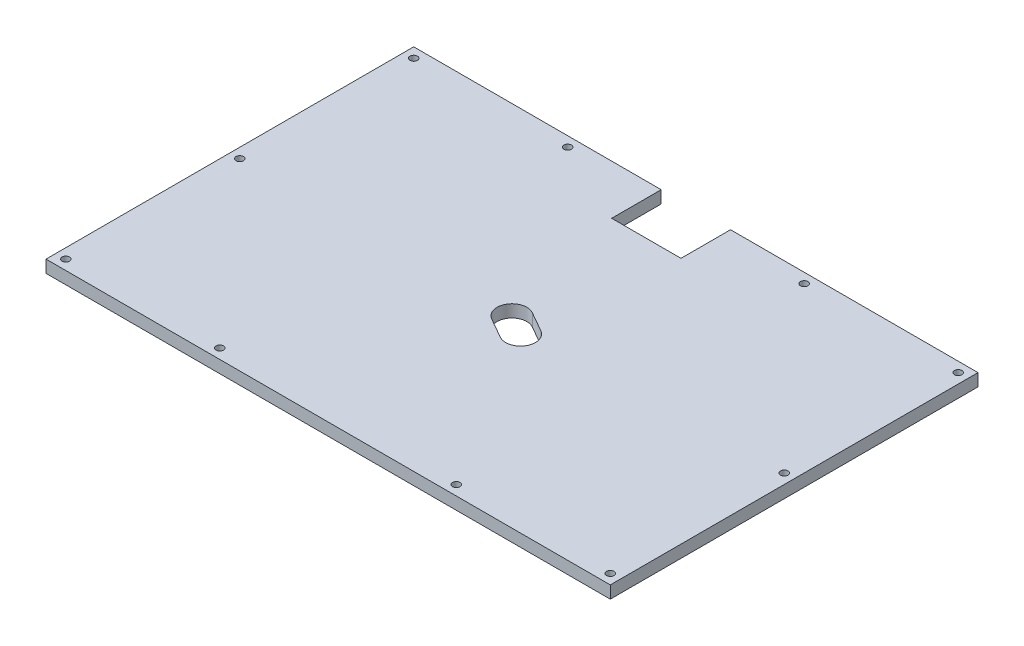
SolidWorks part; units mm, degrees
ref_plane "Front Plane" through (0, 0, 0) normal (0, 0, 1) x (1, 0, 0)
ref_plane "Top Plane" through (0, 0, 0) normal (0, 1, 0) x (1, 0, 0)
ref_plane "Right Plane" through (0, 0, 0) normal (1, 0, 0) x (0, 0, -1)
sketch "Sketch1" plane through (0, 0, 0) normal (0, 1, 0) x (1, 0, 0)
  line L0 (4, 74.24) -> (4, 18.24) construction
  line L1 (4, 74.24) -> (4, 130.24) construction
  line L2 (113.93, 128.48) -> (113.93, 74.24) construction
  line L3 (4, 4) -> (4, -27.1102) construction
  line L4 (4, -27.1102) -> (122, -27.1102) construction
  line L5 (122, 4) -> (122, 69.637) construction
  line L6 (124.9727, 74.8488) -> (116.9027, 79.4518)
  line L7 (122, 69.637) -> (113.93, 74.24) construction
  line L8 (119.0273, 64.4252) -> (110.9573, 69.0282)
  line L19 (0, 0) -> (0, 148.48)
  line L20 (227.86, 148.48) -> (127.93, 148.48)
  line L21 (227.86, 0) -> (0, 0)
  line L22 (223.86, 144.48) -> (223.86, 148.48) construction
  line L23 (223.86, 144.48) -> (227.86, 144.48) construction
  line L24 (223.86, 144.48) -> (161.68, 144.48) construction
  line L25 (161.68, 144.48) -> (66.18, 144.48) construction
  line L26 (227.86, 148.48) -> (227.86, 0)
  line L27 (66.18, 144.48) -> (4, 144.48) construction
  line L28 (4, 144.48) -> (4, 4) construction
  line L29 (4, 4) -> (223.86, 4) construction
  line L30 (223.86, 4) -> (223.86, 144.48) construction
  line L31 (161.68, 144.48) -> (161.68, 4) construction
  line L32 (66.18, 4) -> (66.18, 144.48) construction
  line L33 (0, 0) -> (227.86, 148.48) construction
  line L34 (99.93, 148.48) -> (0, 148.48)
  line L36 (99.93, 148.48) -> (99.93, 128.48)
  line L37 (99.93, 128.48) -> (127.93, 128.48)
  line L38 (127.93, 128.48) -> (127.93, 148.48)
  arc A2 (119.0273, 64.4252) -> (124.9727, 74.8488) centre (122, 69.637) ccw
  circle A7 centre (223.86, 74.24) radius 1.5
  circle A8 centre (4, 74.24) radius 1.5
  circle A9 centre (66.18, 4) radius 1.5
  circle A10 centre (161.68, 4) radius 1.5
  circle A11 centre (161.68, 144.48) radius 1.5
  circle A16 centre (66.18, 144.48) radius 1.5
  circle A17 centre (223.86, 4) radius 1.5
  circle A18 centre (4, 4) radius 1.5
  circle A19 centre (4, 144.48) radius 1.5
  circle A20 centre (223.86, 144.48) radius 1.5
  arc A21 (116.9027, 79.4518) -> (110.9573, 69.0282) centre (113.93, 74.24) ccw
  dimension "D4" = 118
  dimension "D3" = 95.5
  dimension "D6" = 65.637
  dimension "D8" = 6
  dimension "D14" = 3
  dimension "D23" = 3
  dimension "D24" = 12
  dimension "D9" = 9.2905
  dimension "D5" = 56
  dimension "D7" = 56
  dimension "D15" = 62.18
  dimension "D17" = 62.18
  dimension "D18" = 140.48
  dimension "D19" = 148.48
  dimension "D20" = 227.86
  dimension "D21" = 4
  dimension "D22" = 4
  dimension "D25" = 20
  dimension "D26" = 28
extrude "Boss-Extrude1" add sketch "Sketch1" along normal blind 5
